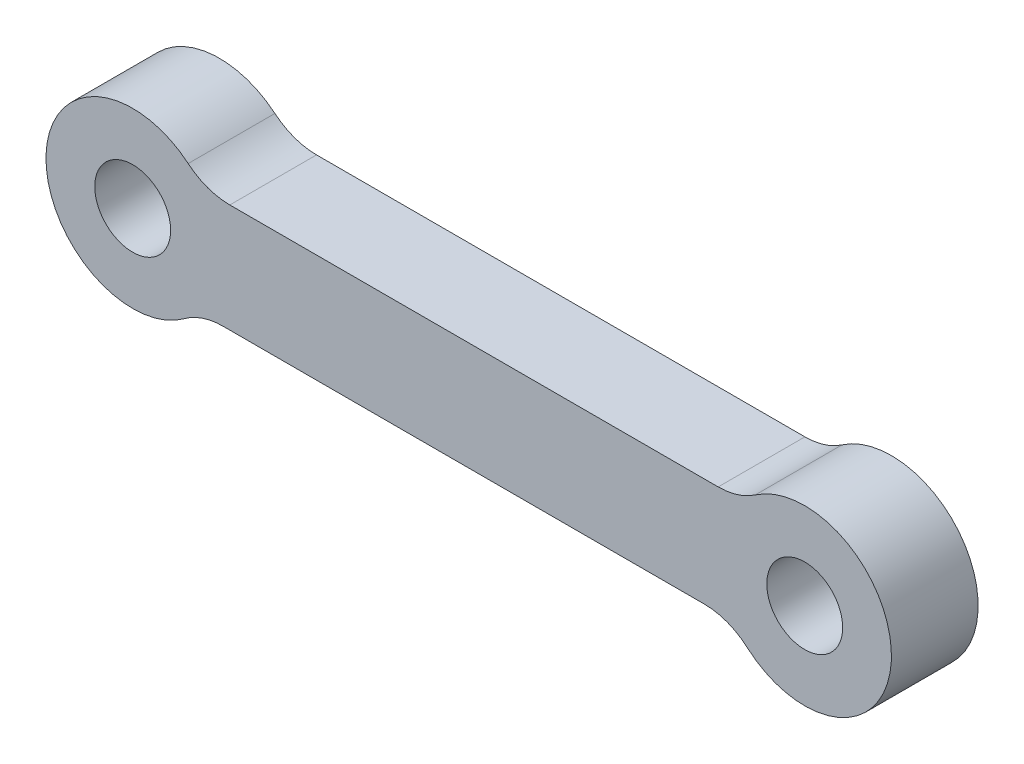
SolidWorks part; units mm, degrees
ref_plane "前视基准面" through (0, 0, 0) normal (0, 0, 1) x (1, 0, 0)
ref_plane "上视基准面" through (0, 0, 0) normal (0, 1, 0) x (1, 0, 0)
ref_plane "右视基准面" through (0, 0, 0) normal (1, 0, 0) x (0, 0, -1)
sketch "草图1" plane through (0, 0, 0) normal (0, 0, 1) x (1, 0, 0)
  line L0 (-10.6529, 2.5) -> (11.8738, 2.5)
  line L1 (-10.9621, -2.5) -> (11.2335, -2.5)
  arc A0 (-12.573, 3.195) -> (-12.7497, -3.0907) centre (-15.1331, 0.1216) ccw
  arc A1 (13.2183, -3.2504) -> (13.5841, 3.0353) centre (15.8646, -0.2509) ccw
  circle A2 centre (-15.1331, 0.1216) radius 1.75
  circle A3 centre (15.8646, -0.2509) radius 1.75
  arc A4 (13.2183, -3.2504) -> (11.2335, -2.5) centre (11.2335, -5.5) ccw
  arc A5 (-12.7497, -3.0907) -> (-10.9621, -2.5) centre (-10.9621, -5.5) cw
  arc A6 (11.8738, 2.5) -> (13.5841, 3.0353) centre (11.8738, 5.5) ccw
  arc A7 (-10.6529, 2.5) -> (-12.573, 3.195) centre (-10.6529, 5.5) cw
  dimension "D3" = 8
  dimension "D4" = 8
  dimension "D5" = 3.5
  dimension "D6" = 3.5
  dimension "D7" = 3
  dimension "D1" = 2.5
  dimension "D2" = 2.5
  dimension "D8" = 31
extrude "凸台-拉伸1" add sketch "草图1" along normal blind 4
